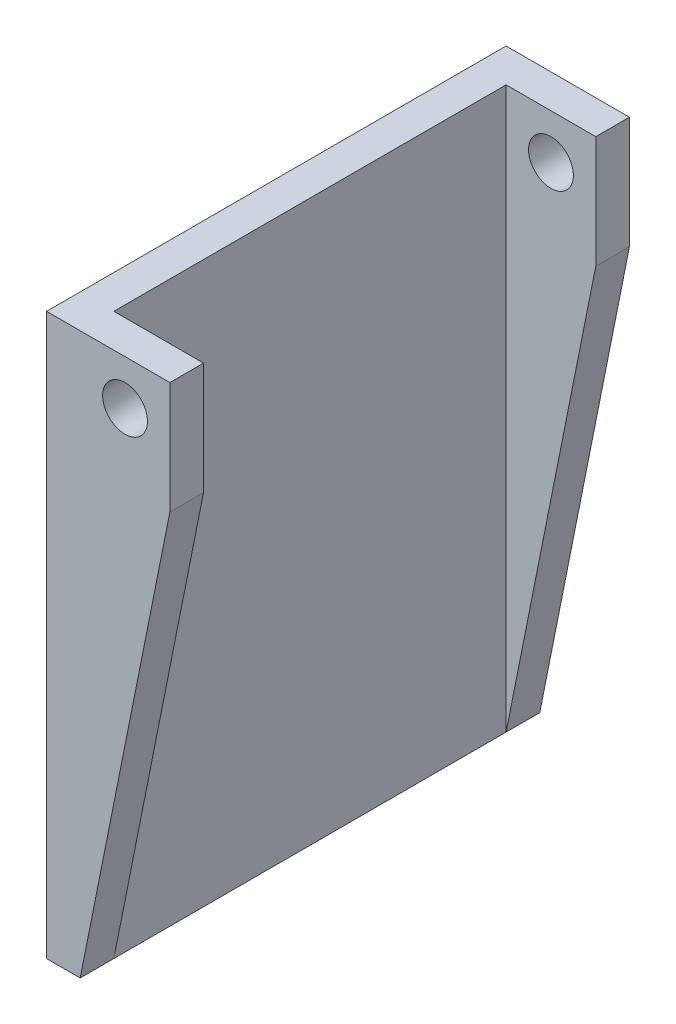
SolidWorks part; units mm, degrees
ref_plane "Front Plane" through (0, 0, 0) normal (0, 0, 1) x (1, 0, 0)
ref_plane "Top Plane" through (0, 0, 0) normal (0, 1, 0) x (1, 0, 0)
ref_plane "Right Plane" through (0, 0, 0) normal (1, 0, 0) x (0, 0, -1)
sketch "Sketch1" plane through (0, 0, 0) normal (1, 0, 0) x (0, 0, -1)
  line L1 (-20.4955, 25) -> (20.4955, 25)
  line L2 (-20.4955, 25) -> (-20.4955, -25)
  line L3 (-20.4955, -25) -> (20.4955, -25)
  line L4 (20.4955, 25) -> (20.4955, -25)
  line L5 (-20.4955, 25) -> (20.4955, -25) construction
  line L6 (-20.4955, -25) -> (20.4955, 25) construction
  point P0 (0, 0)
  dimension "D1" = 50
extrude "Boss-Extrude1" add sketch "Sketch1" along normal blind 3
sketch "Sketch3" plane through (0, 0, 20.4955) normal (0, 0, 1) x (1, 0, 0)
  line L0 (3, 25) -> (11, 25)
  line L1 (11, 25) -> (11, 15)
  line L2 (11, 15) -> (3, -25)
  line L3 (3, 25) -> (3, -25)
  dimension "D1" = 8
  dimension "D2" = 10
extrude "Boss-Extrude3" add sketch "Sketch3" against normal blind 3
sketch "Sketch4" plane through (0, 0, 20.4955) normal (0, 0, 1) x (1, 0, 0)
  line L0 (11, 25) -> (0, 25) construction
  line L1 (11, 15) -> (11, 25) construction
  circle A0 centre (7, 21) radius 2
  point P2 (0, 0)
  dimension "D1" = 4
  dimension "D2" = 4
extrude "Cut-Extrude1" cut sketch "Sketch4" against normal blind 3
mirror "Mirror1" about plane through (0, 0, 0) normal (0, 0, 1) of "Boss-Extrude3", "Cut-Extrude1"
